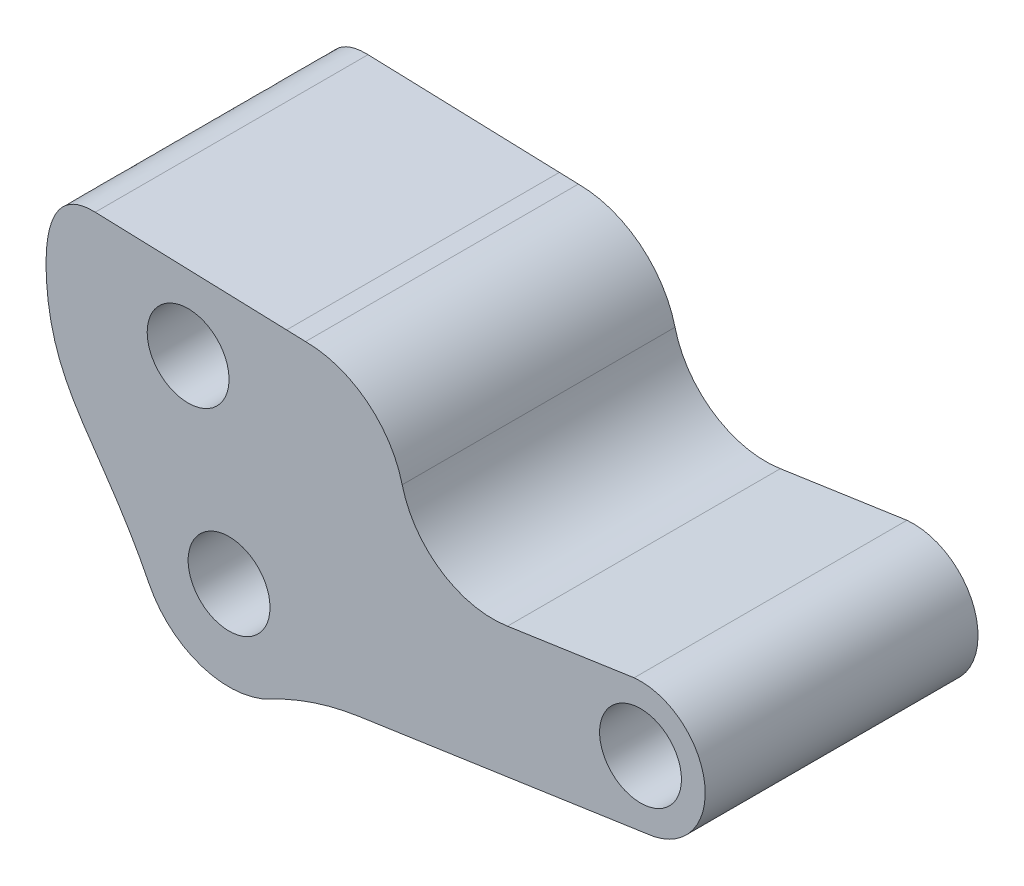
SolidWorks part; units mm, degrees
material "ABS"
ref_plane "Plan de face" through (0, 0, 0) normal (0, 0, 1) x (1, 0, 0)
ref_plane "Plan de dessus" through (0, 0, 0) normal (0, 1, 0) x (1, 0, 0)
ref_plane "Plan de droite" through (0, 0, 0) normal (1, 0, 0) x (0, 0, -1)
sketch "Esquisse1" plane through (0, 0, 0) normal (0, 0, 1) x (1, 0, 0)
  line L0 (149.5318, 51.5092) -> (223.8317, 51.3982) construction
  line L1 (155.9898, 142.1718) -> (159.8152, 142.4642) construction
  line L2 (166.1158, 145.9197) -> (170.8376, 146.614)
  line L3 (160.775, 140.3475) -> (171.3049, 141.8958)
  line L4 (155.9898, 142.1718) -> (156.7978, 143.4356) construction
  line L5 (158.7934, 151.2642) -> (151.0836, 151.517)
  line L6 (155.9898, 142.1718) -> (151.3164, 148.4902) construction
  circle A0 centre (155.9898, 142.1718) radius 1.5
  circle A1 centre (171.0712, 144.2549) radius 1.5
  arc A2 (171.3049, 141.8958) -> (170.8376, 146.614) centre (171.0712, 144.2549) ccw
  arc A3 (153.059, 140.7084) -> (157.5295, 139.2804) centre (155.9898, 142.1718) ccw
  arc A4 (162.3361, 148.4902) -> (158.7934, 151.2642) centre (158.7934, 147.615) ccw
  arc A5 (162.3361, 148.4902) -> (166.1961, 145.9315) centre (165.6582, 149.3109) ccw
  arc A6 (157.5295, 139.2804) -> (160.775, 140.3475) centre (162.2297, 130.4539) cw
  spline S0 degree 3 poles (151.0836, 151.517) (149.3425, 151.5741) (148.8417, 145.3686) (151.2841, 144.2631) (153.059, 140.7084) knots 0 0 0 0 0.305759 1 1 1 1
  spline S1 degree 3 poles (158.0975, 151.287) (158.3259, 151.2726) (158.5578, 151.2642) (158.7934, 151.2642) knots 0.972871 0.972871 0.972871 0.972871 1 1 1 1
  point P4 (163.4323, 143.2442)
  point P10 (157.4858, 144.8742)
  dimension "D2" = 3
  dimension "D3" = 3
  dimension "D1" = 10
extrude "Boss.-Extru.1" add sketch "Esquisse1" along normal blind 10 contours A4 L5 A3 A6 L3 A2 L2 A5 A0 A1
sketch "Esquisse4" plane through (0, 0, 0) normal (0, 0, -1) x (-1, 0, 0)
  circle A0 centre (-154.4886, 148.6604) radius 1.5
extrude "Enlèv. mat.-Extru.1" cut sketch "Esquisse4" against normal blind 10
